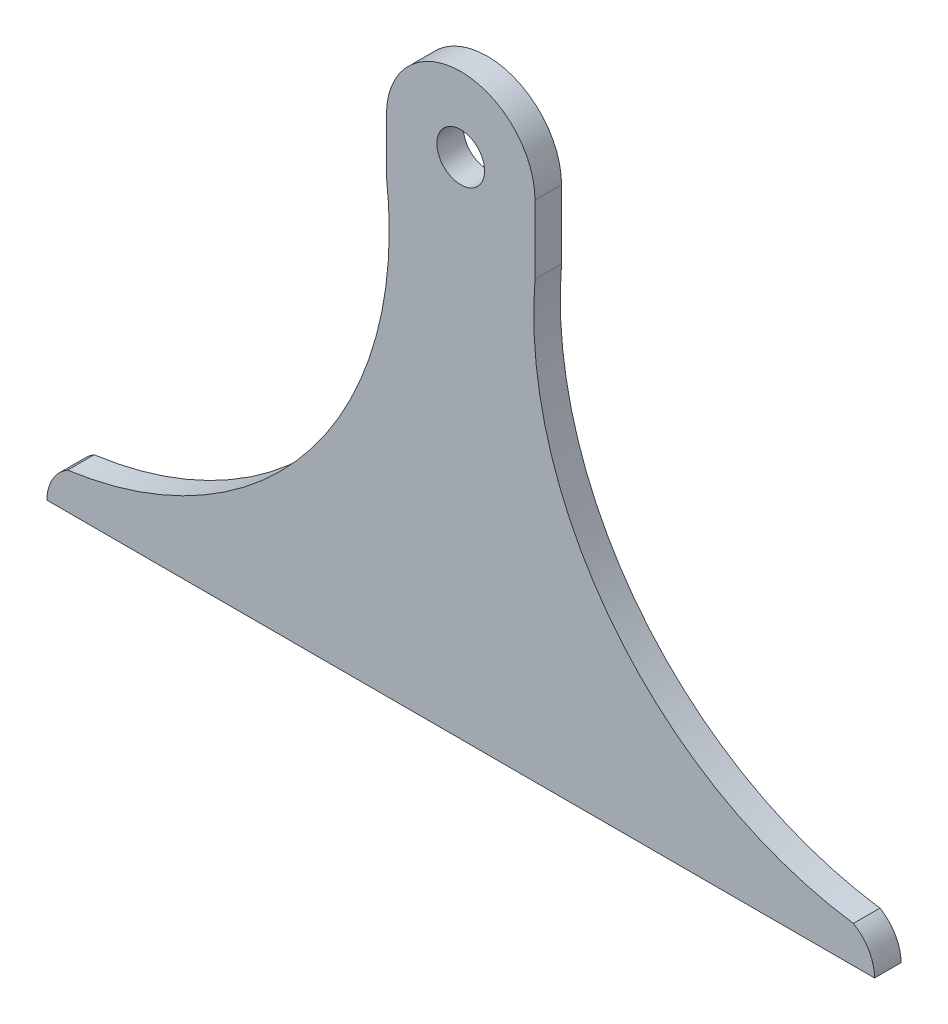
SolidWorks part; units mm, degrees
ref_plane "Front Plane" through (0, 0, 0) normal (0, 0, 1) x (1, 0, 0)
ref_plane "Top Plane" through (0, 0, 0) normal (0, 1, 0) x (1, 0, 0)
ref_plane "Right Plane" through (0, 0, 0) normal (1, 0, 0) x (0, 0, -1)
sketch "Sketch1" plane through (0, 0, 0) normal (0, 0, 1) x (1, 0, 0)
  line L0 (0, 0) -> (0, -4.5) construction
  line L1 (0, 0) -> (33.8894, 0) construction
  line L2 (33.8894, 0) -> (33.8894, -14) construction
  line L3 (33.8894, -14) -> (-41.875, -14) construction
  line L4 (0, -95) -> (70, -95) construction
  line L5 (0, -95) -> (-70, -95) construction
  line L6 (-78, -95) -> (78, -95)
  line L7 (70, -95) -> (70, -79.65) construction
  line L8 (70, -103) -> (70, -114.6394) construction
  line L9 (-70, -95) -> (-70, -74.4153) construction
  line L10 (-70, -103) -> (-70, -111.6088) construction
  line L11 (-70, -87) -> (70, -87)
  line L12 (14, 0) -> (14, -14)
  line L13 (-14, 0) -> (-14, -14)
  line L14 (14, -14) -> (14, -87) construction
  line L15 (-14, -14) -> (-14, -87) construction
  line L16 (0, -14) -> (0, -95) construction
  line L17 (-14, -14) -> (14, -14)
  circle A0 centre (0, 0) radius 4.5
  arc A1 (14, 0) -> (-14, 0) centre (0, 0) ccw
  arc A2 (78, -95) -> (68.653, -87.1142) centre (70, -95) ccw
  arc A3 (-68.4995, -87.142) -> (-78, -95) centre (-70, -95) ccw
  arc A4 (14, -12.9257) -> (74.0181, -88.0823) centre (83.7562, -18.7629) ccw
  arc A5 (-74.1035, -88.1326) -> (-14, -10.218) centre (-83.4765, -18.7629) ccw
extrude "Boss-Extrude1" add sketch "Sketch1" along normal blind 5 contours A5 L11 A4 L17 | A5 A3 L6 A2 A4 L11 | A5 L17 A4 L12 A1 L13 A0
